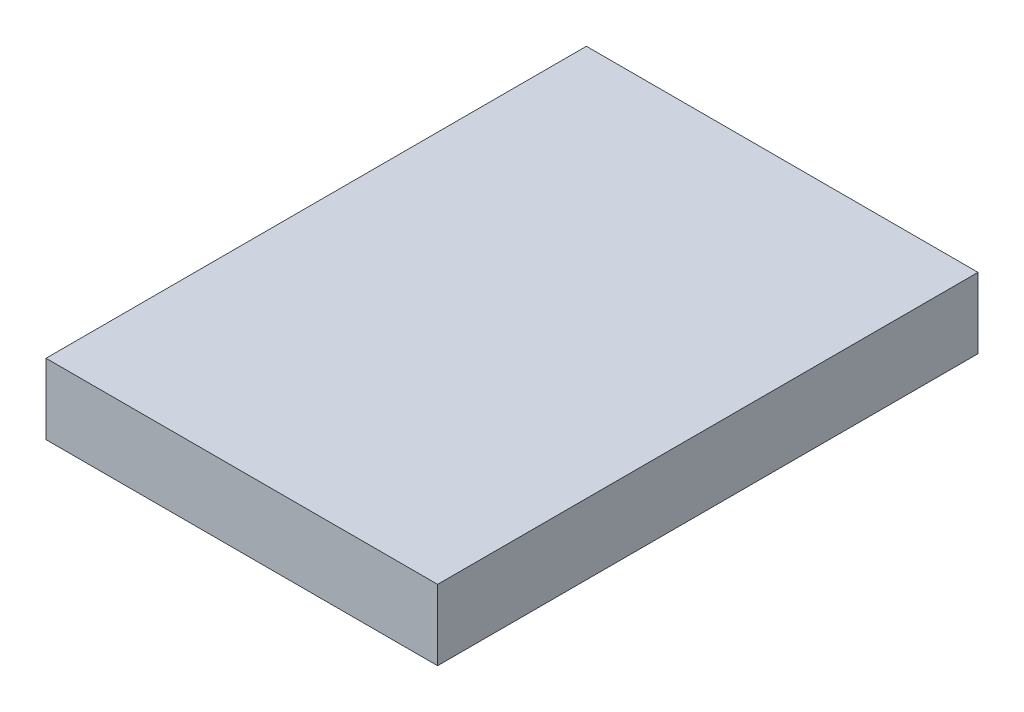
SolidWorks part; units mm, degrees
material "Perspex (TM) GS Acrylic Cast Sheet"
ref_plane "Front Plane" through (0, 0, 0) normal (0, 0, 1) x (1, 0, 0)
ref_plane "Top Plane" through (0, 0, 0) normal (0, 1, 0) x (1, 0, 0)
ref_plane "Right Plane" through (0, 0, 0) normal (1, 0, 0) x (0, 0, -1)
sketch "Sketch1" plane through (0, 0, 0) normal (0, 1, 0) x (1, 0, 0)
  line L1 (-12.5, -17.25) -> (12.5, -17.25)
  line L2 (-12.5, -17.25) -> (-12.5, 17.25)
  line L3 (-12.5, 17.25) -> (12.5, 17.25)
  line L4 (12.5, -17.25) -> (12.5, 17.25)
  line L5 (-12.5, -17.25) -> (12.5, 17.25) construction
  line L6 (-12.5, 17.25) -> (12.5, -17.25) construction
  point P0 (0, 0)
  point P5 (0, 0)
  dimension "D1" = 25
  dimension "D2" = 34.5
extrude "Boss-Extrude1" add sketch "Sketch1" along normal blind 4.5
